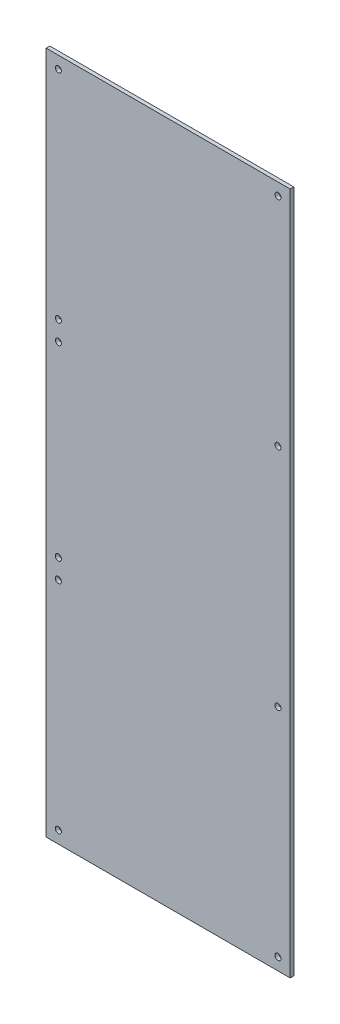
SolidWorks part; units mm, degrees
material "Acrylic (Medium-high impact)"
ref_plane "Front Plane" through (0, 0, 0) normal (0, 0, 1) x (1, 0, 0)
ref_plane "Top Plane" through (0, 0, 0) normal (0, 1, 0) x (1, 0, 0)
ref_plane "Right Plane" through (0, 0, 0) normal (1, 0, 0) x (0, 0, -1)
sketch "Sketch1" plane through (0, 0, 0) normal (0, 0, 1) x (1, 0, 0)
  line L1 (-34.359, 84.1026) -> (165.641, 84.1026)
  line L2 (-34.359, 84.1026) -> (-34.359, -475.8974)
  line L3 (-34.359, -475.8974) -> (165.641, -475.8974)
  line L4 (165.641, 84.1026) -> (165.641, -475.8974)
  dimension "D1" = 200
  dimension "D2" = 560
extrude "Boss-Extrude1" add sketch "Sketch1" along normal blind 3
sketch "Sketch2" plane through (0, 0, 3) normal (0, 0, 1) x (1, 0, 0)
  line L0 (165.641, 84.1026) -> (-34.359, 84.1026) construction
  line L1 (-34.359, 84.1026) -> (-34.359, -475.8974) construction
  line L2 (165.641, -475.8974) -> (165.641, 84.1026) construction
  line L3 (-34.359, -475.8974) -> (165.641, -475.8974) construction
  circle A0 centre (-24.359, 74.1026) radius 2.5
  circle A1 centre (155.641, 74.1026) radius 2.5
  circle A3 centre (-24.359, -465.8974) radius 2.5
  circle A4 centre (155.641, -465.8974) radius 2.5
  circle A5 centre (-24.359, -288.3974) radius 2.5
  circle A6 centre (-24.359, -103.3974) radius 2.5
  circle A7 centre (155.641, -103.3974) radius 2.5
  circle A8 centre (155.641, -288.3974) radius 2.5
  circle A9 centre (-24.359, -119.3974) radius 2.5
  circle A10 centre (-24.359, -272.3974) radius 2.5
  dimension "D1" = 5
  dimension "D3" = 10
  dimension "D5" = 10
  dimension "D6" = 10
  dimension "D7" = 10
  dimension "D8" = 5
  dimension "D9" = 5
  dimension "D10" = 10
  dimension "D11" = 10
  dimension "D12" = 10
  dimension "D14" = 10
  dimension "D15" = 177.5
  dimension "D16" = 10
  dimension "D17" = 177.5
  dimension "D18" = 10
  dimension "D19" = 177.5
  dimension "D20" = 10
  dimension "D22" = 10
  dimension "D23" = 16
  dimension "D2" = 10
  dimension "D4" = 10
  dimension "D13" = 177.5
  dimension "D21" = 16
extrude "Cut-Extrude1" cut sketch "Sketch2" against normal through all
